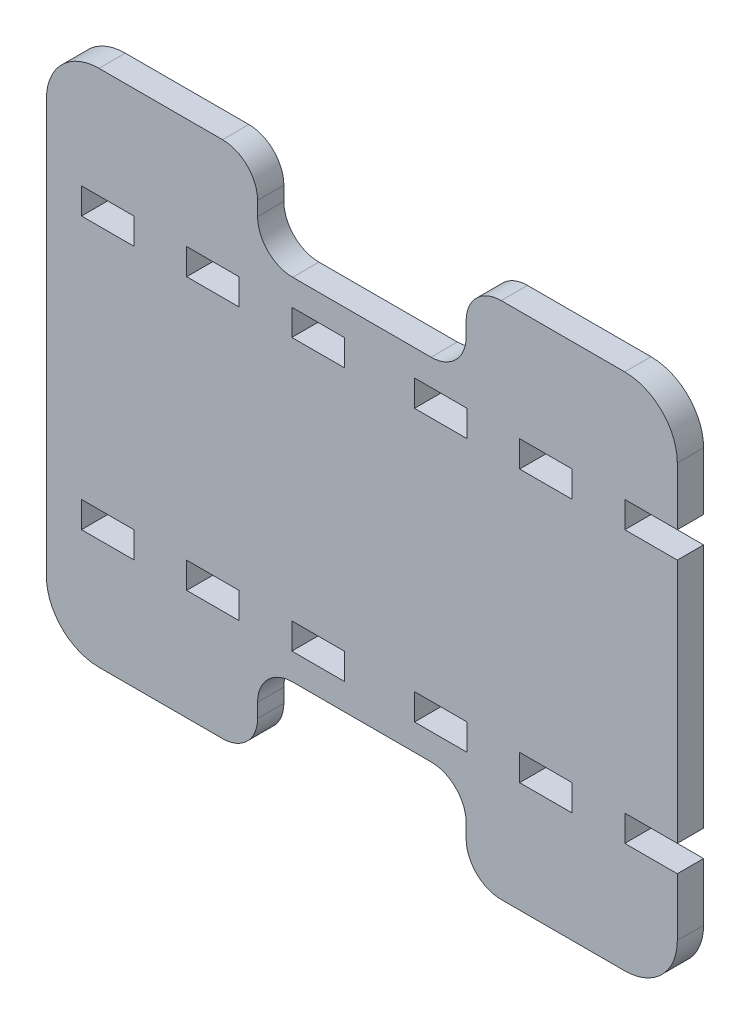
SolidWorks part; units mm, degrees
ref_plane "Front Plane" through (0, 0, 0) normal (0, 0, 1) x (1, 0, 0)
ref_plane "Top Plane" through (0, 0, 0) normal (0, 1, 0) x (1, 0, 0)
ref_plane "Right Plane" through (0, 0, 0) normal (1, 0, 0) x (0, 0, -1)
sketch "Sketch1" plane through (0, 0, 0) normal (0, 0, 1) x (1, 0, 0)
  line L0 (169.9656, 70) -> (-190.0344, 70) construction
  line L1 (-10.0344, 170) -> (-10.0344, -78) construction
  line L2 (169.9656, 188) -> (169.9656, 0)
  line L3 (139.9656, -78) -> (69.4656, -78)
  line L4 (-190.0344, 188) -> (-190.0344, -48)
  line L5 (-10.0344, -30) -> (-10.0344, 218) construction
  line L6 (-140, 0) -> (-170, 0) construction
  line L7 (140, 155) -> (140, 140)
  line L8 (-89.5344, -78) -> (-160.0344, -78)
  line L9 (-69.5344, -58) -> (-69.5344, -50)
  line L10 (-20, -15) -> (-50, -15) construction
  line L11 (-49.5344, -30) -> (29.4656, -30)
  line L12 (49.4656, -58) -> (49.4656, -50)
  line L13 (49.4656, 198) -> (49.4656, 190)
  line L14 (-49.5344, 170) -> (29.4656, 170)
  line L15 (-69.5344, 198) -> (-69.5344, 190)
  line L16 (-89.5344, 218) -> (-160.0344, 218)
  line L17 (139.9656, 218) -> (69.4656, 218)
  line L18 (-140, -14.9652) -> (-170, -14.9652)
  line L19 (-140, -14.9652) -> (-140, -0.0292)
  line L20 (-140, -0.0292) -> (-170, -0.0292)
  line L21 (-170, -14.9652) -> (-170, -0.0292)
  line L22 (-80, -14.9652) -> (-110, -14.9652)
  line L23 (-80, -14.9652) -> (-80, -0.0292)
  line L24 (-80, -0.0292) -> (-110, -0.0292)
  line L25 (-110, -14.9652) -> (-110, -0.0292)
  line L26 (-20, -14.9652) -> (-50, -14.9652)
  line L27 (-20, -14.9652) -> (-20, -0.0292)
  line L28 (-20, -0.0292) -> (-50, -0.0292)
  line L29 (-50, -14.9652) -> (-50, -0.0292)
  line L30 (110, -15) -> (80, -15)
  line L31 (50, -15) -> (20, -15)
  line L32 (50, -15) -> (50, 0)
  line L33 (50, 0) -> (20, 0)
  line L34 (20, -15) -> (20, 0)
  line L35 (110, -15) -> (110, 0)
  line L36 (110, 0) -> (80, 0)
  line L37 (80, -15) -> (80, 0)
  line L38 (170, -15) -> (140, -15)
  line L39 (170, 140) -> (140, 140)
  line L40 (170, 0) -> (140, 0)
  line L41 (140, -15) -> (140, 0)
  line L42 (170, 155) -> (140, 155)
  line L43 (80, 155) -> (80, 140)
  line L44 (110, 140) -> (80, 140)
  line L45 (110, 155) -> (110, 140)
  line L46 (20, 155) -> (20, 140)
  line L47 (50, 140) -> (20, 140)
  line L48 (50, 155) -> (50, 140)
  line L49 (50, 155) -> (20, 155)
  line L50 (110, 155) -> (80, 155)
  line L51 (-50, 154.9652) -> (-50, 140.0292)
  line L52 (-20, 140.0292) -> (-50, 140.0292)
  line L53 (-20, 154.9652) -> (-20, 140.0292)
  line L54 (-20, 154.9652) -> (-50, 154.9652)
  line L55 (-110, 154.9652) -> (-110, 140.0292)
  line L56 (-80, 140.0292) -> (-110, 140.0292)
  line L57 (-80, 154.9652) -> (-80, 140.0292)
  line L58 (-80, 154.9652) -> (-110, 154.9652)
  line L59 (-170, 154.9652) -> (-170, 140.0292)
  line L60 (-140, 140.0292) -> (-170, 140.0292)
  line L61 (-140, 154.9652) -> (-140, 140.0292)
  line L62 (-140, 154.9652) -> (-170, 154.9652)
  line L65 (-140, -15) -> (-140, 0) construction
  line L67 (-170, -15) -> (-170, 155) construction
  line L68 (40, -14.9652) -> (10, -14.9652) [skipped]
  line L69 (40, -14.9652) -> (40, -0.0292) [skipped]
  line L70 (40, -0.0292) -> (10, -0.0292) [skipped]
  line L71 (10, -14.9652) -> (10, -0.0292) [skipped]
  line L72 (100, -14.9652) -> (70, -14.9652) [skipped]
  line L73 (100, -14.9652) -> (100, -0.0292) [skipped]
  line L74 (100, -0.0292) -> (70, -0.0292) [skipped]
  line L75 (70, -14.9652) -> (70, -0.0292) [skipped]
  line L76 (160, -14.9652) -> (130, -14.9652) [skipped]
  line L77 (160, -14.9652) -> (160, -0.0292) [skipped]
  line L78 (160, -0.0292) -> (130, -0.0292) [skipped]
  line L79 (130, -14.9652) -> (130, -0.0292) [skipped]
  line L80 (169.9656, -15) -> (169.9656, -48)
  line L81 (170, -15) -> (170, 0) [skipped]
  arc A0 (69.4656, -78) -> (49.4656, -58) centre (69.4656, -58) cw
  arc A1 (-89.5344, -78) -> (-69.5344, -58) centre (-89.5344, -58) ccw
  arc A2 (-69.5344, -50) -> (-49.5344, -30) centre (-49.5344, -50) cw
  arc A3 (29.4656, -30) -> (49.4656, -50) centre (29.4656, -50) cw
  arc A4 (29.4656, 170) -> (49.4656, 190) centre (29.4656, 190) ccw
  arc A5 (-69.5344, 190) -> (-49.5344, 170) centre (-49.5344, 190) ccw
  arc A6 (-89.5344, 218) -> (-69.5344, 198) centre (-89.5344, 198) cw
  arc A7 (69.4656, 218) -> (49.4656, 198) centre (69.4656, 198) ccw
  arc A8 (-190.0344, -48) -> (-160.0344, -78) centre (-160.0344, -48) ccw
  arc A9 (-190.0344, 188) -> (-160.0344, 218) centre (-160.0344, 188) cw
  arc A10 (139.9656, 218) -> (169.9656, 188) centre (139.9656, 188) cw
  arc A11 (139.9656, -78) -> (169.9656, -48) centre (139.9656, -48) ccw
  point P16 (49.4656, -78)
  point P19 (-69.5344, -78)
  point P22 (-69.5344, -30)
  point P25 (49.4656, -30)
  point P44 (49.4656, 170)
  point P45 (-69.5344, 170)
  point P46 (-69.5344, 218)
  point P47 (49.4656, 218)
  point P50 (-190.0344, -78)
  point P53 (-190.0344, 218)
  point P56 (169.9656, 218)
  point P59 (169.9656, -78)
  dimension "D3" = 20
  dimension "D5" = 30
  dimension "D1" = 296
  dimension "D2" = 70
  dimension "D4" = 15
  dimension "D6" = 360
  dimension "D7" = 159
  dimension "D8" = 6
  dimension "D9" = 3
extrude "Boss-Extrude1" add sketch "Sketch1" along normal blind 15
